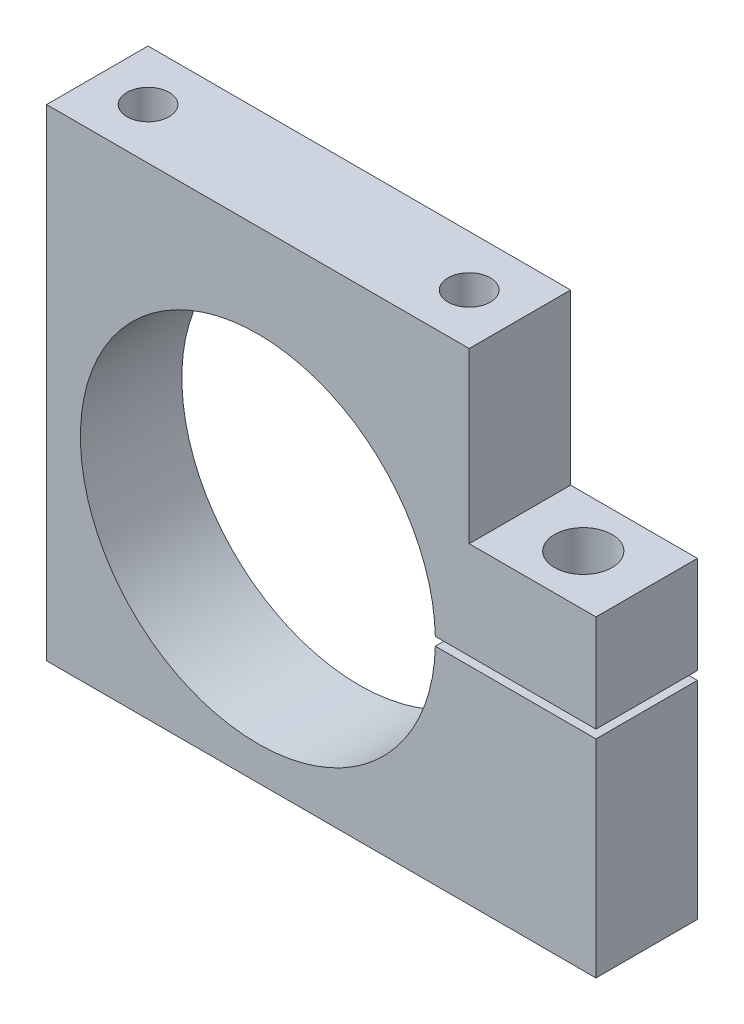
SolidWorks part; units mm, degrees
material "7075-T6, Chapa (SS)"
ref_plane "Plano frontal" through (0, 0, 0) normal (0, 0, 1) x (1, 0, 0)
ref_plane "Plano superior" through (0, 0, 0) normal (0, 1, 0) x (1, 0, 0)
ref_plane "Plano direito" through (0, 0, 0) normal (1, 0, 0) x (0, 0, -1)
sketch "Esboço1" plane through (0, 0, 0) normal (0, 0, 1) x (1, 0, 0)
  line L2 (0, 0) -> (0, 57)
  line L5 (0, 57) -> (50, 57)
  line L6 (50, 57) -> (50, 37)
  line L7 (50, 37) -> (65, 37)
  line L12 (0, 0) -> (65, 0)
  line L13 (65, 37) -> (65, 0)
  circle A1 centre (25, 25) radius 21
  dimension "D3" = 37
  dimension "D4" = 25
  dimension "D2" = 42
  dimension "D1" = 57
  dimension "D5" = 20
  dimension "D6" = 15
  dimension "D8" = 25
  dimension "D9" = 50
extrude "Ressalto-extrusão1" add sketch "Esboço1" along normal blind 12
sketch "Esboço2" plane through (0, 0, 12) normal (0, 0, 1) x (1, 0, 0)
  line L0 (45, 25.5) -> (65, 25.5)
  line L1 (65, 25.5) -> (65, 24.5)
  line L2 (65, 24.5) -> (45, 24.5)
  line L3 (45, 24.5) -> (45, 25.5)
  line L4 (65, 0) -> (65, 37) construction
  line L5 (65, 25) -> (-6.1725, 25) construction
  line L6 (0, 0) -> (65, 0) construction
  point P8 (65, 25)
  dimension "D1" = 1
  dimension "D2" = 20
  dimension "D3" = 25
extrude "Corte-extrusão1" cut sketch "Esboço2" against normal through all
hole_wizard "Broca de rosquear para tarraxa de M81" positions "Esboço3" profile "Esboço4" hole size "M8" standard "ISO"
sketch "Esboço3" plane through (0, 37, 0) normal (0, 1, 0) x (1, 0, 0)
  line L0 (57.5, 0) -> (57.5, -12) construction
  line L1 (65, 0) -> (50, 0) construction
  line L2 (65, -12) -> (50, -12) construction
  point P0 (57.5, -6)
sketch "Esboço4" plane through (57.5, 37, 6) normal (1, 0, 0) x (0, 0, 1)
  line L0 (0, 0) -> (0, 27.0429)
  line L1 (0, 27.0429) -> (3.4, 25)
  line L2 (3.4, 25) -> (3.4, 0)
  line L5 (3.4, 0) -> (0, 0)
  line L10 (0, 27.0429) -> (-3.4, 25) construction
  line L11 (0, -6.35) -> (0, 107.95) construction
  dimension "Hole Dia." = 6.8
  dimension "Hole Depth" = 25
  dimension "Drill Angle" = 118
hole_wizard "Broca de rosquear para tarraxa de M62" positions "Esboço5" profile "Esboço6" hole size "M6" standard "ISO"
sketch "Esboço5" plane through (0, 57, 0) normal (0, 1, 0) x (1, 0, 0)
  line L0 (0, -12) -> (0, 0) construction
  line L1 (50, -12) -> (50, 0) construction
  line L2 (0, -6) -> (50, -6) construction
  point P0 (6, -6)
  point P2 (44, -6)
  dimension "D1" = 6
  dimension "D2" = 6
sketch "Esboço6" plane through (6, 57, 6) normal (1, 0, 0) x (0, 0, 1)
  line L0 (0, 0) -> (0, 16.5022)
  line L1 (0, 16.5022) -> (2.5, 15)
  line L2 (2.5, 15) -> (2.5, 0)
  line L5 (2.5, 0) -> (0, 0)
  line L10 (0, 16.5022) -> (-2.5, 15) construction
  line L11 (0, -6.35) -> (0, 107.95) construction
  dimension "Hole Dia." = 5
  dimension "Hole Depth" = 15
  dimension "Drill Angle" = 118
hole_wizard "Broca de rosquear para tarraxa de M63" positions "Esboço7" profile "Esboço8" hole size "M6" standard "ISO"
sketch "Esboço7" plane through (0, 0, 0) normal (0, -1, 0) x (-1, 0, 0)
  line L0 (-65, -6) -> (0, -6) construction
  line L1 (-65, -12) -> (-65, 0) construction
  line L2 (0, -12) -> (0, 0) construction
  point P0 (-4, -6)
  point P2 (-48, -6)
  dimension "D1" = 17
  dimension "D2" = 4
sketch "Esboço8" plane through (4, 0, 6) normal (1, 0, 0) x (0, 0, -1)
  line L0 (0, 0) -> (0, 16.5022)
  line L1 (0, 16.5022) -> (2.5, 15)
  line L2 (2.5, 15) -> (2.5, 0)
  line L5 (2.5, 0) -> (0, 0)
  line L10 (0, 16.5022) -> (-2.5, 15) construction
  line L11 (0, -6.35) -> (0, 107.95) construction
  dimension "Hole Dia." = 5
  dimension "Hole Depth" = 15
  dimension "Drill Angle" = 118
